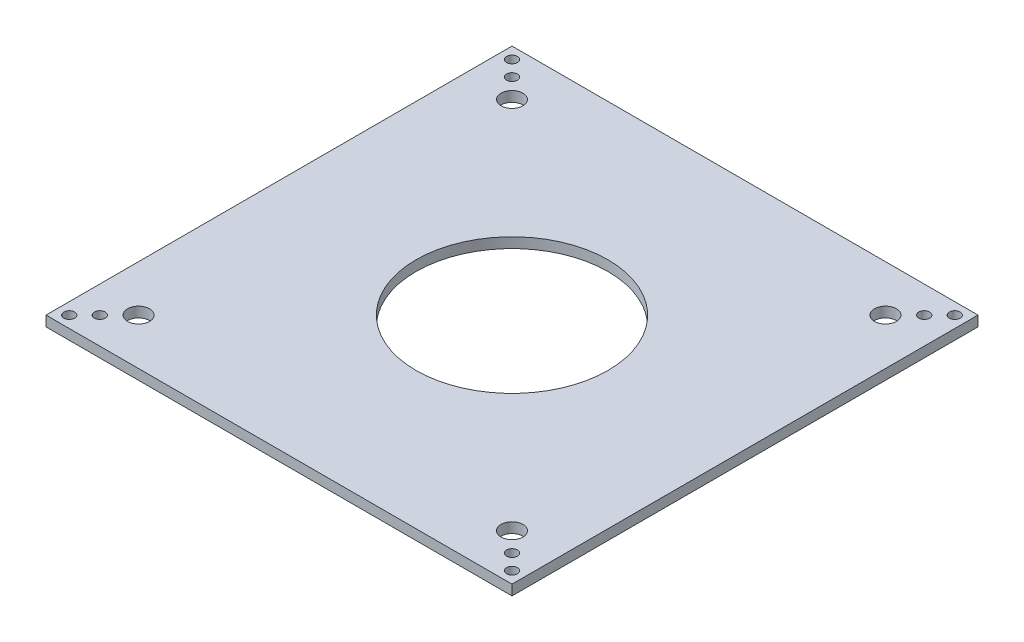
SolidWorks part; units mm, degrees
ref_plane "Front Plane" through (0, 0, 0) normal (0, 0, 1) x (1, 0, 0)
ref_plane "Top Plane" through (0, 0, 0) normal (0, 1, 0) x (1, 0, 0)
ref_plane "Right Plane" through (0, 0, 0) normal (1, 0, 0) x (0, 0, -1)
sketch "Sketch1" plane through (0, 0, 0) normal (0, 1, 0) x (1, 0, 0)
  line L0 (0, 0) -> (107.95, -107.95) construction
  line L1 (-107.95, 107.95) -> (107.95, 107.95)
  line L2 (-107.95, 107.95) -> (-107.95, -107.95)
  line L3 (-107.95, -107.95) -> (107.95, -107.95)
  line L4 (107.95, 107.95) -> (107.95, -107.95)
  circle A0 centre (95.4908, -95.4908) radius 2.5
  circle A1 centre (102.5618, -102.5618) radius 2.5
  circle A2 centre (-95.4908, -95.4908) radius 2.5
  circle A3 centre (-102.5618, -102.5618) radius 2.5
  circle A4 centre (-95.4908, 95.4908) radius 2.5
  circle A5 centre (-102.5618, 102.5618) radius 2.5
  circle A6 centre (95.4908, 95.4908) radius 2.5
  circle A7 centre (102.5618, 102.5618) radius 2.5
  circle A12 centre (86.5105, -86.5105) radius 5.08
  circle A13 centre (-86.5105, -86.5105) radius 5.08
  circle A14 centre (-86.5105, 86.5105) radius 5.08
  circle A15 centre (86.5105, 86.5105) radius 5.08
  circle A16 centre (0, 0) radius 44.45
  point P4 (0, 107.95)
  point P28 (0, 0)
  point P34 (0, 0)
  point P37 (0, 0)
  point P40 (107.95, 0)
  dimension "D3" = 5
  dimension "D4" = 5
  dimension "D7" = 10.16
  dimension "D10" = 88.9
  dimension "D1" = 215.9
  dimension "D2" = 10
  dimension "D5" = 7.62
  dimension "D8" = 12.7
  dimension "D9" = 4
  dimension "D6" = 4
extrude "Boss-Extrude1" add sketch "Sketch1" along normal blind 4.7498
sketch "Sketch3" plane through (0, 0, 0) normal (0, 0, 1) x (1, 0, 0)
  line L0 (0, 0) -> (0, 25.4) construction
  line L1 (-107.95, 0) -> (107.95, 0) construction
  dimension "D1" = 25.4
ref_plane "Plane1" through (0, 0, 0) normal (0.7071, 0, -0.7071) x (0, 1, 0)
